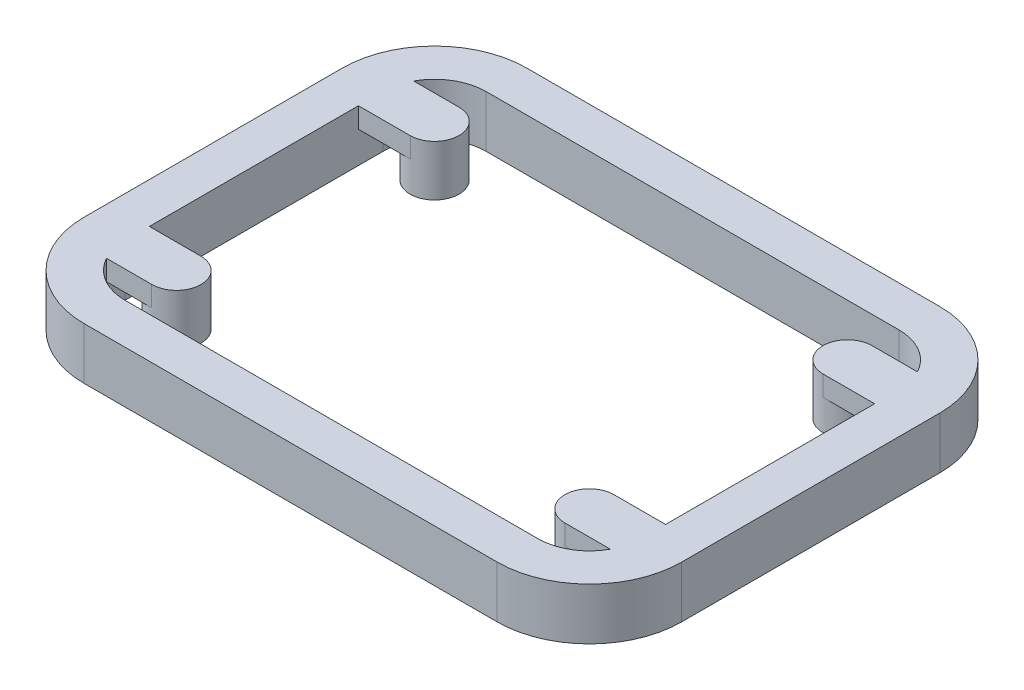
SolidWorks part; units mm, degrees
ref_plane "Front Plane" through (0, 0, 0) normal (0, 0, 1) x (1, 0, 0)
ref_plane "Top Plane" through (0, 0, 0) normal (0, 1, 0) x (1, 0, 0)
ref_plane "Right Plane" through (0, 0, 0) normal (1, 0, 0) x (0, 0, -1)
sketch "Sketch1" plane through (0, 0, 0) normal (0, 1, 0) x (1, 0, 0)
  line L0 (-14.7, 6.35) -> (-14.7, -6.35)
  line L1 (-10.16, 8.89) -> (10.16, 8.89)
  line L2 (-12.7, 6.35) -> (-12.7, -6.35)
  line L3 (-10.16, -8.89) -> (10.16, -8.89)
  line L4 (12.7, 6.35) -> (12.7, -6.35)
  line L5 (-12.7, 8.89) -> (12.7, -8.89) construction
  line L6 (-12.7, -8.89) -> (12.7, 8.89) construction
  line L7 (-10.16, -10.89) -> (10.16, -10.89)
  line L8 (14.7, 6.35) -> (14.7, -6.35)
  line L9 (-10.16, 10.89) -> (10.16, 10.89)
  arc A0 (-12.7, -6.35) -> (-10.16, -8.89) centre (-10.16, -6.35) ccw
  arc A1 (10.16, -8.89) -> (12.7, -6.35) centre (10.16, -6.35) ccw
  arc A2 (10.16, 8.89) -> (12.7, 6.35) centre (10.16, 6.35) cw
  arc A3 (-10.16, 8.89) -> (-12.7, 6.35) centre (-10.16, 6.35) ccw
  arc A4 (-14.7, -6.35) -> (-10.16, -10.89) centre (-10.16, -6.35) ccw
  arc A5 (10.16, -10.89) -> (14.7, -6.35) centre (10.16, -6.35) ccw
  arc A6 (10.16, 10.89) -> (14.7, 6.35) centre (10.16, 6.35) cw
  arc A7 (-10.16, 10.89) -> (-14.7, 6.35) centre (-10.16, 6.35) ccw
  point P0 (0, 0)
  dimension "D3" = 2.54
  dimension "D1" = 17.78
  dimension "D2" = 25.4
  dimension "D4" = 2
extrude "Boss-Extrude1" add sketch "Sketch1" along normal blind 2.55
sketch "Sketch2" plane through (0, 2.55, 0) normal (0, 1, 0) x (1, 0, 0)
  line L1 (-10.16, 6.35) -> (10.16, 6.35) construction
  line L2 (-10.16, 6.35) -> (-10.16, -6.35) construction
  line L3 (-10.16, -6.35) -> (10.16, -6.35) construction
  line L4 (10.16, 6.35) -> (10.16, -6.35) construction
  line L5 (-10.16, 6.35) -> (10.16, -6.35) construction
  line L6 (-10.16, -6.35) -> (10.16, 6.35) construction
  circle A0 centre (10.16, 6.35) radius 1.2065
  circle A1 centre (-10.16, 6.35) radius 1.2065
  circle A2 centre (-10.16, -6.35) radius 1.2065
  circle A3 centre (10.16, -6.35) radius 1.2065
  point P0 (0, 0)
  dimension "D3" = 2.413
  dimension "D4" = 2.413
  dimension "D5" = 2.413
  dimension "D6" = 2.413
  dimension "D1" = 12.7
  dimension "D2" = 20.32
extrude "Boss-Extrude2" add sketch "Sketch2" against normal blind 2.5 separate body
sketch "Sketch3" plane through (0, 2.55, 0) normal (0, 1, 0) x (1, 0, 0)
  line L2 (-12.7, 6.35) -> (-12.7, -6.35) construction
  line L3 (0, 8.89) -> (0, -8.89) construction
  line L4 (10.16, 8.89) -> (-10.16, 8.89) construction
  line L5 (-10.16, -8.89) -> (10.16, -8.89) construction
  line L6 (-15, 0) -> (12.7, 0) construction
  line L7 (12.7, -6.35) -> (12.7, 6.35) construction
  line L28 (-10.1493, 7.5565) -> (-12.7, 7.5565)
  line L29 (-10.1493, 7.5565) -> (-10.1493, 5.1435)
  line L30 (-10.1493, 5.1435) -> (-12.7, 5.1435)
  line L31 (-12.7, 7.5565) -> (-12.7, 5.1435)
  line L32 (10.1493, 5.1435) -> (12.7, 5.1435)
  line L33 (12.7, 7.5565) -> (12.7, 5.1435)
  line L34 (10.1493, 7.5565) -> (12.7, 7.5565)
  line L35 (10.1493, 7.5565) -> (10.1493, 5.1435)
  line L36 (10.1493, -7.5565) -> (10.1493, -5.1435)
  line L37 (10.1493, -7.5565) -> (12.7, -7.5565)
  line L38 (12.7, -7.5565) -> (12.7, -5.1435)
  line L39 (10.1493, -5.1435) -> (12.7, -5.1435)
  line L40 (-10.1493, -5.1435) -> (-12.7, -5.1435)
  line L41 (-12.7, -7.5565) -> (-12.7, -5.1435)
  line L42 (-10.1493, -7.5565) -> (-12.7, -7.5565)
  line L43 (-10.1493, -7.5565) -> (-10.1493, -5.1435)
  circle A4 centre (-10.16, 6.35) radius 1.2065 construction
  dimension "D1" = 2.413
extrude "Boss-Extrude3" add sketch "Sketch3" against normal blind 1
